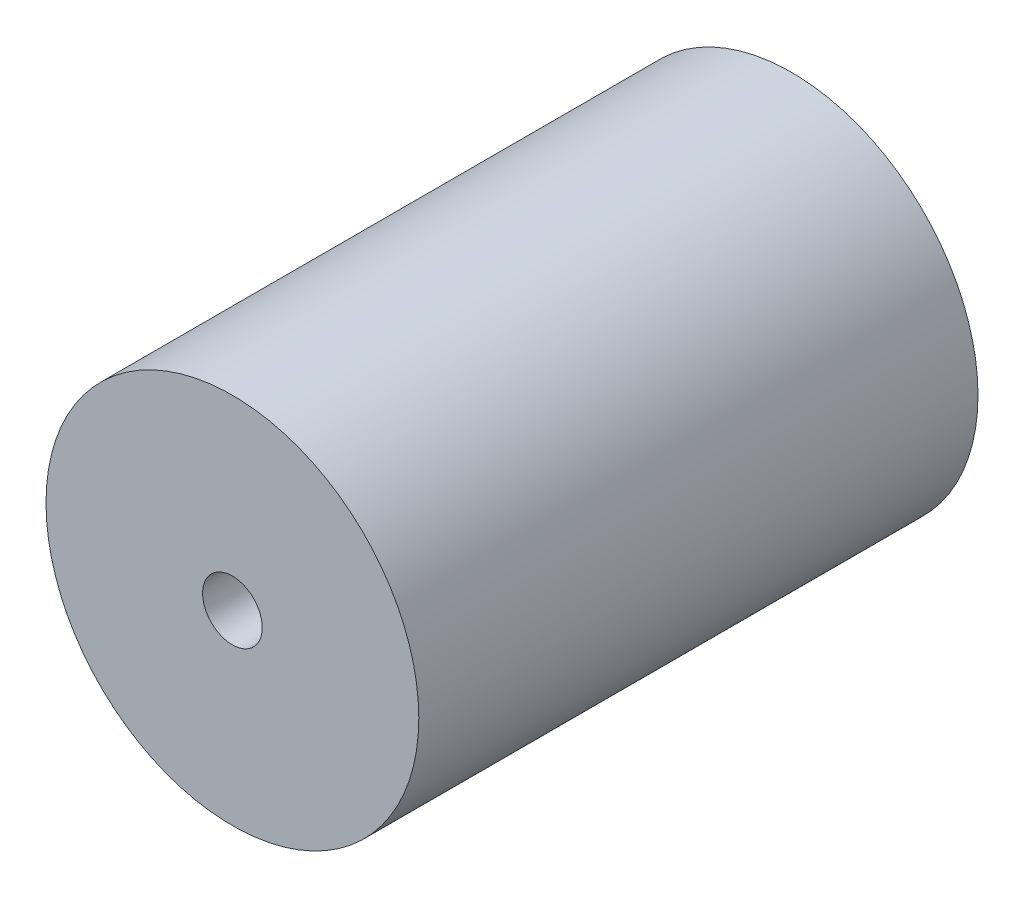
SolidWorks part; units mm, degrees
ref_plane "前视基准面" through (0, 0, 0) normal (0, 0, 1) x (1, 0, 0)
ref_plane "上视基准面" through (0, 0, 0) normal (0, 1, 0) x (1, 0, 0)
ref_plane "右视基准面" through (0, 0, 0) normal (1, 0, 0) x (0, 0, -1)
sketch "草图1" plane through (0, 0, 0) normal (0, 0, 1) x (1, 0, 0)
  circle A0 centre (0, 0) radius 25
  dimension "D1" = 50
extrude "凸台-拉伸1" add sketch "草图1" along normal blind 100
sketch "草图3" plane through (0, 0, 100) normal (0, 0, 1) x (1, 0, 0)
  circle A0 centre (0, 0) radius 4
  dimension "D1" = 8
extrude "切除-拉伸1" cut sketch "草图3" against normal blind 8
sketch "草图4" plane through (0, 0, 0) normal (0, 0, -1) x (-1, 0, 0)
  circle A0 centre (0, 0) radius 25
extrude "切除-拉伸2" cut sketch "草图4" against normal blind 25
